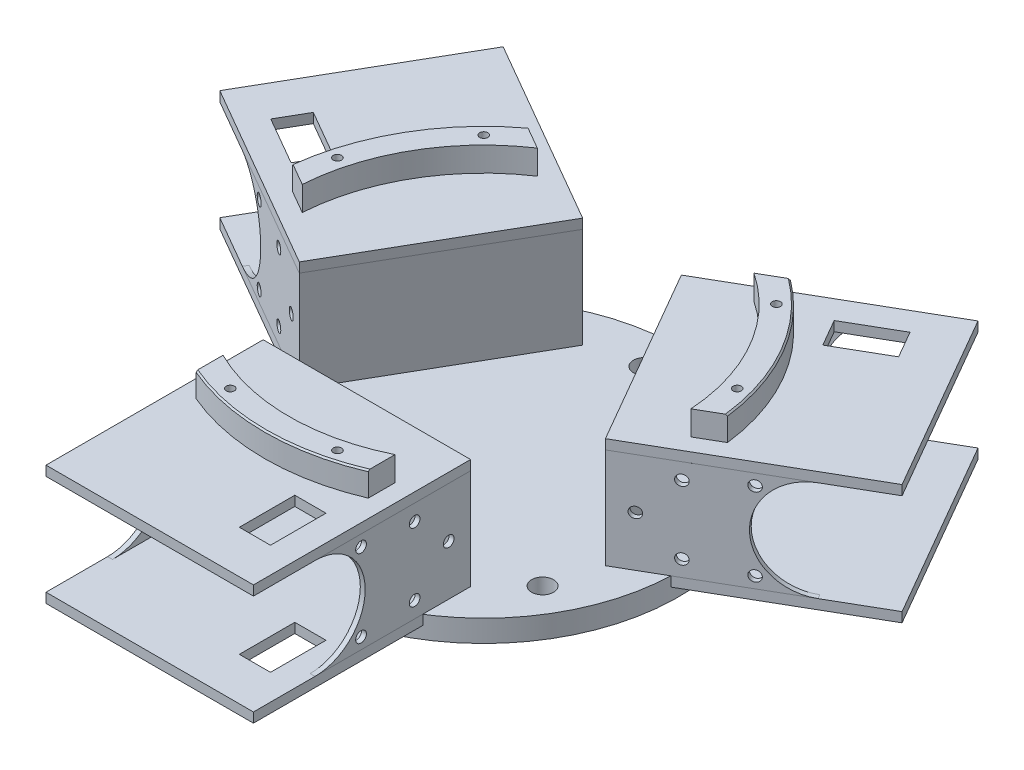
SolidWorks part; units mm, degrees
ref_plane "前视基准面" through (0, 0, 0) normal (0, 0, 1) x (1, 0, 0)
ref_plane "上视基准面" through (0, 0, 0) normal (0, 1, 0) x (1, 0, 0)
ref_plane "右视基准面" through (0, 0, 0) normal (1, 0, 0) x (0, 0, -1)
other "Configuration Table"
sketch "草图1" plane through (0, 0, 0) normal (0, 1, 0) x (1, 0, 0)
  circle A0 centre (0, 0) radius 40
  dimension "D1" = 80
extrude "凸台-拉伸1" add sketch "草图1" against normal blind 4.5
sketch "草图2" plane through (0, 0, 0) normal (0, 1, 0) x (1, 0, 0)
  line L0 (0, 0) -> (0, -40.2791) construction
  line L1 (-20.3, -26) -> (20.3, -26)
  line L2 (20.3, -26) -> (20.3, -66.6)
  line L3 (20.3, -66.6) -> (-20.3, -66.6)
  line L5 (-21.3, -26) -> (-21.3, -24)
  line L6 (-21.3, -24) -> (21.3, -24)
  line L7 (21.3, -24) -> (21.3, -68.6)
  line L8 (21.3, -68.6) -> (-21.3, -68.6)
  line L9 (-21.3, -68.6) -> (-21.3, -66.2)
  line L10 (-20.3, -26) -> (-20.3, -66.6)
  line L11 (-21.3, -26) -> (-21.3, -66.2)
  dimension "D1" = 20.3
  dimension "D2" = 20.3
  dimension "D3" = 1
  dimension "D4" = 2
  dimension "D5" = 2
  dimension "D6" = 24
  dimension "D7" = 40.6
  dimension "D8" = 1
extrude "凸台-拉伸2" add sketch "草图2" along normal blind 20.6 separate body
sketch "草图3" plane through (0, 20.6, 0) normal (0, 1, 0) x (1, 0, 0)
  line L0 (-21.3, -68.6) -> (-21.3, -24)
  line L8 (-21.3, -24) -> (-21.3, -68.6)
  line L13 (-21.3, -68.6) -> (21.3, -68.6)
  line L14 (21.3, -68.6) -> (21.3, -24)
  line L15 (21.3, -24) -> (-21.3, -24)
  line L21 (-21.3, -68.6) -> (21.3, -68.6)
  line L22 (21.3, -68.6) -> (21.3, -24)
  line L23 (21.3, -24) -> (-21.3, -24)
  dimension "D1" = 0
extrude "凸台-拉伸3" add sketch "草图3" along normal blind 2 separate body
sketch "草图4" plane through (0, 0, 0) normal (0, 1, 0) x (1, 0, 0)
  line L4 (21.3, -24) -> (-21.3, -24)
  line L5 (-21.3, -24) -> (-21.3, -68.6)
  line L6 (-21.3, -68.6) -> (21.3, -68.6)
  line L7 (21.3, -68.6) -> (21.3, -24)
  line L8 (21.3, -24) -> (-21.3, -24)
  line L9 (-21.3, -24) -> (-21.3, -68.6)
  line L10 (-21.3, -68.6) -> (21.3, -68.6)
  line L11 (21.3, -68.6) -> (21.3, -24)
  dimension "D1" = 0
extrude "凸台-拉伸4" add sketch "草图4" against normal blind 2 separate body
sketch "草图6" plane through (0, 22.6, 0) normal (0, 1, 0) x (1, 0, 0)
  line L0 (0, -19.5948) -> (0, -85.4434) construction
  line L1 (-17.6683, -35.8864) -> (-17.6683, -41.3864)
  line L2 (17.6683, -35.8864) -> (17.6683, -41.3864)
  line L4 (21.3, -24) -> (-21.3, -24)
  line L5 (-21.3, -24) -> (-21.3, -68.6)
  line L6 (-21.3, -68.6) -> (21.3, -68.6)
  line L7 (21.3, -68.6) -> (21.3, -24)
  line L8 (21.3, -24) -> (-21.3, -24)
  line L9 (-21.3, -24) -> (-21.3, -68.6)
  line L10 (-21.3, -68.6) -> (21.3, -68.6)
  line L11 (21.3, -68.6) -> (21.3, -24)
  arc A0 (-17.6683, -35.8864) -> (17.6683, -35.8864) centre (0, 0) ccw
  arc A1 (-17.6683, -41.3864) -> (17.6683, -41.3864) centre (0, 0) ccw
  dimension "D2" = 40
  dimension "D3" = 45
  dimension "D4" = 5.5
  dimension "D5" = 5.5
  dimension "D1" = 0
extrude "凸台-拉伸5" add sketch "草图6" along normal blind 5 contours A0 L0 A1 L2 | L0 A0 L1 A1
sketch "草图7" plane through (0, 27.6, 0) normal (0, 1, 0) x (1, 0, 0)
  line L0 (0, 0) -> (0, -59.3747) construction
  arc A0 (-10.9998, -41.0518) -> (10.9998, -41.0518) centre (0, 0) ccw
  dimension "D1" = 42.5
  dimension "D2" = 30
hole_wizard "孔1" positions "草图8" profile "草图9" legacy
sketch "草图8" plane through (0, 27.6, 0) normal (0, 1, 0) x (1, 0, 0)
  point P8 (-10.9998, -41.0518)
  point P11 (10.9998, -41.0518)
sketch "草图9" plane through (-10.9998, 27.6, 41.0518) normal (1, 0, 0) x (0, 0, 1)
  line L0 (0, 0) -> (0, 100)
  line L1 (0, 100) -> (0.85, 100)
  line L2 (0.85, 100) -> (0.85, 0)
  line L3 (0.85, 0) -> (0, 0)
  line L4 (0, 110) -> (0, -10) construction
  dimension "直径" = 1.7
  dimension "深度" = 100
chamfer "倒角1" distance 0.3 angle 45 1 edges at (0, 27.6, 45)
sketch "草图10" plane through (21.3, 0, 0) normal (-1, 0, 0) x (0, 0, 1)
  line L0 (1.0118, 10.3) -> (12.1008, 10.3) construction
  line L1 (28.5, 10.3) -> (35.5, 3.3)
  line L2 (35.5, 3.3) -> (46.5, 2.3)
  line L3 (46.5, 2.3) -> (46.5, 18.3)
  line L4 (26, 0) -> (66.6, 0)
  line L5 (66.6, 0) -> (66.6, 20.6)
  line L6 (66.6, 20.6) -> (26, 20.6)
  line L7 (26, 20.6) -> (26, 0)
  line L8 (26, 0) -> (66.6, 0)
  line L9 (66.6, 0) -> (66.6, 20.6)
  line L10 (66.6, 20.6) -> (26, 20.6)
  line L11 (26, 20.6) -> (26, 0)
  line L12 (46.5, 18.3) -> (35.5, 17.3)
  line L13 (35.5, 17.3) -> (28.5, 10.3)
  point P6 (46.5, 18.3)
  point P7 (46.5, 2.3)
  point P8 (35.5, 17.3)
  point P9 (35.5, 3.3)
  point P10 (28.5, 10.3)
  point P12 (26, 10.3)
  dimension "D2" = 2.5
  dimension "D3" = 7
  dimension "D4" = 8
  dimension "D5" = 9.5
  dimension "D6" = 20.5
  dimension "D1" = 0
sketch "草图19" plane through (0, 22.6, 0) normal (0, 1, 0) x (1, 0, 0)
  line L1 (9.6, -48.4) -> (16, -48.4)
  line L2 (9.6, -48.4) -> (9.6, -59.8)
  line L3 (9.6, -59.8) -> (16, -59.8)
  line L4 (16, -48.4) -> (16, -59.8)
  line L5 (9.6, -48.4) -> (16, -59.8) construction
  line L6 (9.6, -59.8) -> (16, -48.4) construction
  line L8 (20.3, -26) -> (-20.3, -26)
  line L9 (20.3, -66.6) -> (20.3, -26)
  line L10 (-20.3, -66.6) -> (20.3, -66.6)
  line L11 (-20.3, -26) -> (-20.3, -66.6)
  line L12 (-20.3, -26) -> (-20.3, -66.6)
  line L16 (20.3, -26) -> (-20.3, -26)
  line L17 (20.3, -66.6) -> (20.3, -26)
  line L18 (-20.3, -66.6) -> (20.3, -66.6)
  point P2 (12.8, -54.1)
  dimension "D2" = 6.8
  dimension "D3" = 7.5
  dimension "D4" = 6.4
  dimension "D5" = 11.4
  dimension "D1" = 0
extrude "切除-拉伸2" cut sketch "草图19" against normal through all contours L4 L1 L2 L3
hole_wizard "孔2" positions "草图17" profile "草图18" legacy end condition through all
sketch "草图17" plane through (21.3, 0, 0) normal (1, 0, 0) x (0, 0, -1)
  point P0 (-46.5, 18.3)
  point P3 (-46.5, 2.3)
  point P6 (-35.5, 3.3)
  point P9 (-28.5, 10.3)
  point P12 (-35.5, 17.3)
sketch "草图18" plane through (21.3, 18.3, 46.5) normal (0, 1, 0) x (0, 0, -1)
  line L0 (0, 0) -> (0, 61.3)
  line L1 (0, 61.3) -> (1.1, 61.3)
  line L2 (1.1, 61.3) -> (1.1, 0)
  line L3 (1.1, 0) -> (0, 0)
  line L4 (0, 110) -> (0, -10) construction
  dimension "直径" = 2.2
  dimension "深度" = 61.3
sketch "草图28" plane through (21.3, 0, 0) normal (1, 0, 0) x (0, 0, -1)
  line L0 (-55.95, 10.3) -> (-24, 10.3) construction
  line L4 (-68.6, 0) -> (-24, 0)
  line L5 (-24, 0) -> (-24, 20.6)
  line L6 (-24, 20.6) -> (-68.6, 20.6)
  line L7 (-68.6, 20.6) -> (-68.6, 0)
  line L8 (-68.6, 0) -> (-24, 0)
  line L9 (-24, 0) -> (-24, 20.6)
  line L10 (-24, 20.6) -> (-68.6, 20.6)
  line L16 (-68.6, 0) -> (-68.6, 20.6)
  arc A1 (-55.95, 0) -> (-55.95, 20.6) centre (-55.95, 10.3) ccw
  dimension "D2" = 31.95
  dimension "D1" = 0
extrude "切除-拉伸3" cut sketch "草图28" against normal through all
pattern_circular "阵列(圆周)1" count 3 over 360 about axis through (0, 0, 0) along (0, 1, 0) of bodies 139 146 140 109 120 128
sketch "草图21" plane through (0, -4.5, 0) normal (0, 1, 0) x (1, 0, 0)
  line L0 (0, 0) -> (0, -59.3747) construction
  line L1 (0, 0) -> (-35.66, 20.5883) construction
  line L2 (0, 0) -> (0, -59.3747) construction
  line L3 (0, 0) -> (-35.66, 20.5883) construction
  line L4 (0, 0) -> (-57.1577, -33) construction
  circle A0 centre (0, 0) radius 40 construction
  point P2 (-28.5788, -16.5)
  point P10 (0, 33)
  point P11 (28.5788, -16.5)
  point P12 (0, 0)
  dimension "D1" = 60
  dimension "D2" = 33
  dimension "D3" = 3
hole_wizard "M4 间隙孔1" positions "草图24" profile "草图25" hole size "M4" standard "GB" end condition up to next
sketch "草图24" plane through (0, -4.5, 0) normal (0, -1, 0) x (-1, 0, 0)
  point P0 (-28.5788, -16.5)
  point P3 (28.5788, -16.5)
  point P6 (0, 33)
sketch "草图25" plane through (28.5788, -4.5, 16.5) normal (1, 0, 0) x (0, 0, -1)
  line L0 (0, 0) -> (0, 4.5)
  line L1 (0, 4.5) -> (2.25, 4.5)
  line L2 (2.25, 4.5) -> (2.25, 0.025)
  line L3 (2.25, 0.025) -> (2.275, 0)
  line L5 (2.275, 0) -> (0, 0)
  line L6 (-2.25, 0.025) -> (-2.275, 0) construction
  line L11 (0, -6.35) -> (0, 107.95) construction
  dimension "通孔孔直径" = 4.5
  dimension "通孔孔深度" = 4.5
  dimension "近端锥形沉头孔直径" = 4.55
  dimension "近端锥形沉头孔角度" = 90
